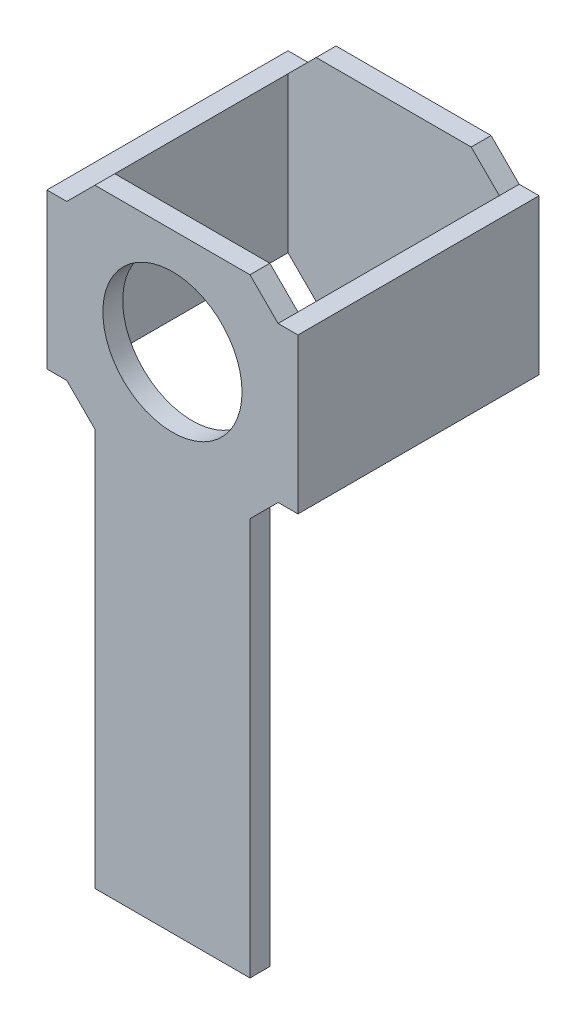
SolidWorks part; units mm, degrees
ref_plane "Front Plane" through (0, 0, 0) normal (1, 0, 0) x (0, 1, 0)
ref_plane "Top Plane" through (0, 0, 0) normal (0, 0, 1) x (0, 1, 0)
ref_plane "Right Plane" through (0, 0, 0) normal (0, 1, 0) x (-1, 0, 0)
sketch "Sketch1" plane through (0, 0, 0) normal (0, 0, 1) x (0, 1, 0)
  line L1 (-21.25, -21.25) -> (21.25, -21.25)
  line L2 (-21.25, -21.25) -> (-21.25, 21.25)
  line L3 (-21.25, 21.25) -> (21.25, 21.25)
  line L4 (21.25, -21.25) -> (21.25, 21.25)
  line L5 (-21.25, -21.25) -> (21.25, 21.25) construction
  line L6 (-21.25, 21.25) -> (21.25, -21.25) construction
  circle A0 centre (0, 0) radius 14
  point P0 (0, 0)
  dimension "D3" = 28
  dimension "D1" = 42.5
  dimension "D2" = 42.5
extrude "Boss-Extrude1" add sketch "Sketch1" along normal blind 4
sketch "Sketch2" plane through (0, 0, 4) normal (0, 0, 1) x (1, 0, 0)
  line L0 (-15.5931, 21.25) -> (-21.25, 15.5931)
  line L1 (21.25, 21.25) -> (-21.25, 21.25) construction
  line L2 (-21.25, 21.25) -> (-21.25, -21.25) construction
  line L3 (-21.25, -15.5931) -> (-15.5931, -21.25)
  line L4 (-21.25, -21.25) -> (21.25, -21.25) construction
  line L5 (15.5931, -21.25) -> (21.25, -15.5931)
  line L6 (21.25, -21.25) -> (21.25, 21.25) construction
  line L7 (15.5931, 21.25) -> (21.25, 15.5931)
  line L8 (0, 0) -> (18.4216, 18.4216) construction
  line L9 (0, 0) -> (21.25, 0) construction
  line L10 (-15.5931, 21.25) -> (-21.25, 21.25)
  line L11 (21.25, -21.25) -> (15.5931, -21.25)
  line L12 (21.25, -21.25) -> (21.25, -15.5931)
  line L13 (21.25, 21.25) -> (15.5931, 21.25)
  line L14 (-21.25, -21.25) -> (-21.25, -15.5931)
  line L15 (21.25, -21.25) -> (-21.25, 21.25) construction
  line L16 (21.25, 21.25) -> (-21.25, -21.25) construction
  line L17 (-21.25, 15.5931) -> (-21.25, 21.25)
  line L18 (-15.5931, -21.25) -> (-21.25, -21.25)
  line L19 (21.25, 15.5931) -> (21.25, 21.25)
  dimension "D1" = 45
  dimension "D2" = 8
extrude "Cut-Extrude1" cut sketch "Sketch2" against normal blind 10
sketch "Sketch3" plane through (-21.25, 0, 0) normal (-1, 0, 0) x (0, -1, 0)
  line L4 (-15.5931, 4) -> (15.5931, 4)
  line L5 (-15.5931, 4) -> (-15.5931, -40.5)
  line L6 (15.5931, 4) -> (15.5931, -40.5)
  line L7 (-15.5931, -40.5) -> (15.5931, -40.5)
  line L8 (-15.5931, 0) -> (15.5931, 0) construction
  dimension "D1" = 40.5
extrude "Boss-Extrude2" add sketch "Sketch3" along normal blind 4
sketch "Sketch4" plane through (21.25, 0, 0) normal (1, 0, 0) x (0, 1, 0)
  line L16 (15.5931, -40.5) -> (15.5931, 4)
  line L17 (-15.5931, -40.5) -> (15.5931, -40.5)
  line L18 (-15.5931, 4) -> (-15.5931, -40.5)
  line L19 (15.5931, 4) -> (-15.5931, 4)
  line L20 (15.5931, -40.5) -> (15.5931, 4)
  line L21 (-15.5931, -40.5) -> (15.5931, -40.5)
  line L22 (-15.5931, 4) -> (-15.5931, -40.5)
  line L23 (15.5931, 4) -> (-15.5931, 4)
  dimension "D2" = 0
extrude "Boss-Extrude3" add sketch "Sketch4" along normal blind 4
sketch "Sketch6" plane through (0, 0, -40.5) normal (0, 0, -1) x (1, 0, 0)
  line L0 (-21.25, 15.5931) -> (-25.25, 15.5931)
  line L1 (-25.25, 15.5931) -> (-25.25, -15.5931)
  line L2 (-25.25, -15.5931) -> (-21.25, -15.5931)
  line L3 (21.25, 15.5931) -> (25.25, 15.5931)
  line L4 (25.25, 15.5931) -> (25.25, -15.5931)
  line L5 (25.25, -15.5931) -> (21.25, -15.5931)
  line L8 (15.5931, -21.25) -> (21.25, -15.5931)
  line L9 (21.25, -15.5931) -> (21.25, 15.5931)
  line L10 (21.25, 15.5931) -> (15.5931, 21.25)
  line L11 (15.5931, 21.25) -> (-15.5931, 21.25)
  line L12 (-15.5931, 21.25) -> (-21.25, 15.5931)
  line L13 (-21.25, 15.5931) -> (-21.25, -15.5931)
  line L14 (-21.25, -15.5931) -> (-15.5931, -21.25)
  line L15 (-15.5931, -21.25) -> (15.5931, -21.25)
  line L16 (15.5931, -21.25) -> (21.25, -15.5931)
  line L18 (21.25, 15.5931) -> (15.5931, 21.25)
  line L19 (15.5931, 21.25) -> (-15.5931, 21.25)
  line L20 (-15.5931, 21.25) -> (-21.25, 15.5931)
  line L22 (-21.25, -15.5931) -> (-15.5931, -21.25)
  line L23 (-15.5931, -21.25) -> (15.5931, -21.25)
  dimension "D1" = 0
extrude "Boss-Extrude5" add sketch "Sketch6" along normal blind 4
sketch "Sketch8" plane through (0, 0, 4) normal (0, 0, 1) x (1, 0, 0)
  line L0 (15.5931, -21.25) -> (-15.5931, -21.25)
  line L1 (15.5931, -21.25) -> (15.5931, -101.25)
  line L2 (-15.5931, -21.25) -> (-15.5931, -101.25)
  line L3 (15.5931, -101.25) -> (-15.5931, -101.25)
  dimension "D1" = 80
extrude "Boss-Extrude6" add sketch "Sketch8" against normal blind 4
